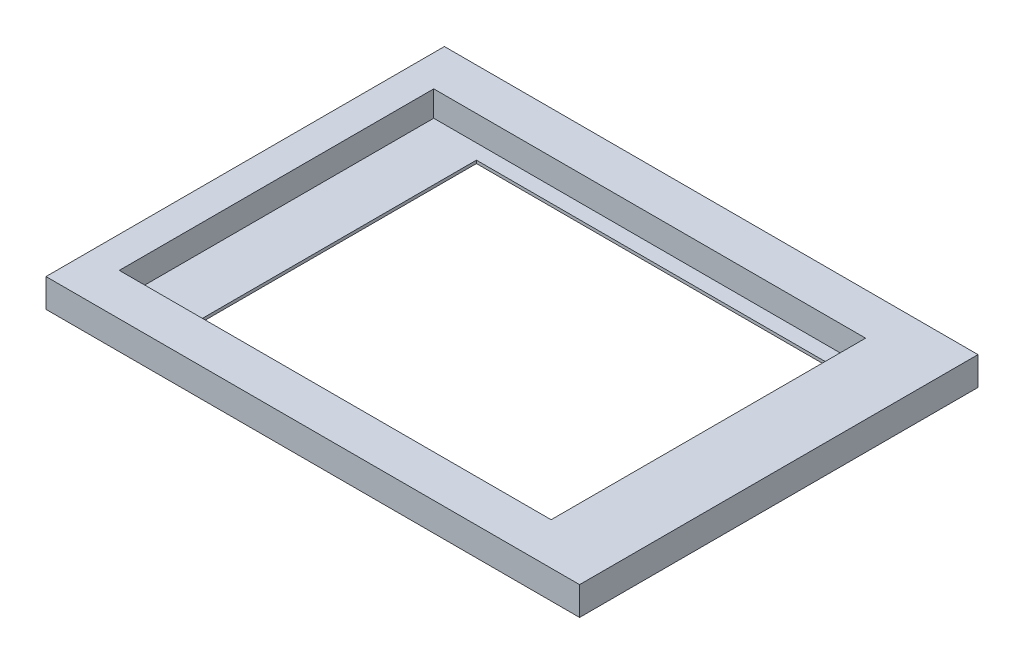
SolidWorks part; units mm, degrees
ref_plane "Plano frontal" through (0, 0, 0) normal (0, 0, 1) x (1, 0, 0)
ref_plane "Plano superior" through (0, 0, 0) normal (0, 1, 0) x (1, 0, 0)
ref_plane "Plano direito" through (0, 0, 0) normal (1, 0, 0) x (0, 0, -1)
sketch "Esboço4" plane through (0, 0, 0) normal (0, 1, 0) x (1, 0, 0)
  line L1 (0, 0) -> (-75, 0)
  line L2 (0, 0) -> (0, 56)
  line L3 (0, 56) -> (-75, 56)
  line L4 (-75, 0) -> (-75, 56)
  dimension "D1" = 75
  dimension "D2" = 56
extrude "Ressalto-extrusão1" add sketch "Esboço4" along normal blind 4
sketch "Esboço5" plane through (0, 4, 0) normal (0, 1, 0) x (1, 0, 0)
  line L0 (-75, 56) -> (-75, 0) construction
  line L1 (-62.5, 48) -> (-12.5, 48)
  line L2 (-62.5, 48) -> (-62.5, 8)
  line L3 (-62.5, 8) -> (-12.5, 8)
  line L4 (-12.5, 48) -> (-12.5, 8)
  line L5 (0, 56) -> (-75, 56) construction
  dimension "D1" = 12.5
  dimension "D2" = 50
  dimension "D3" = 40
  dimension "D4" = 8
extrude "Corte-extrusão1" cut sketch "Esboço5" against normal through all
sketch "Esboço6" plane through (0, 4, 0) normal (0, 1, 0) x (1, 0, 0)
  line L0 (-12.5, 8) -> (-12.5, 48) construction
  line L1 (-70.6, 50.1) -> (-9.9, 50.1)
  line L2 (-70.6, 50.1) -> (-70.6, 5.9)
  line L3 (-70.6, 5.9) -> (-9.9, 5.9)
  line L4 (-9.9, 50.1) -> (-9.9, 5.9)
  line L5 (-12.5, 48) -> (-62.5, 48) construction
  line L6 (-62.5, 48) -> (-62.5, 8) construction
  line L7 (-62.5, 8) -> (-12.5, 8) construction
  dimension "D1" = 2.6
  dimension "D2" = 2.1
  dimension "D3" = 2.1
  dimension "D4" = 8.1
extrude "Corte-extrusão2" cut sketch "Esboço6" against normal blind 3.58
